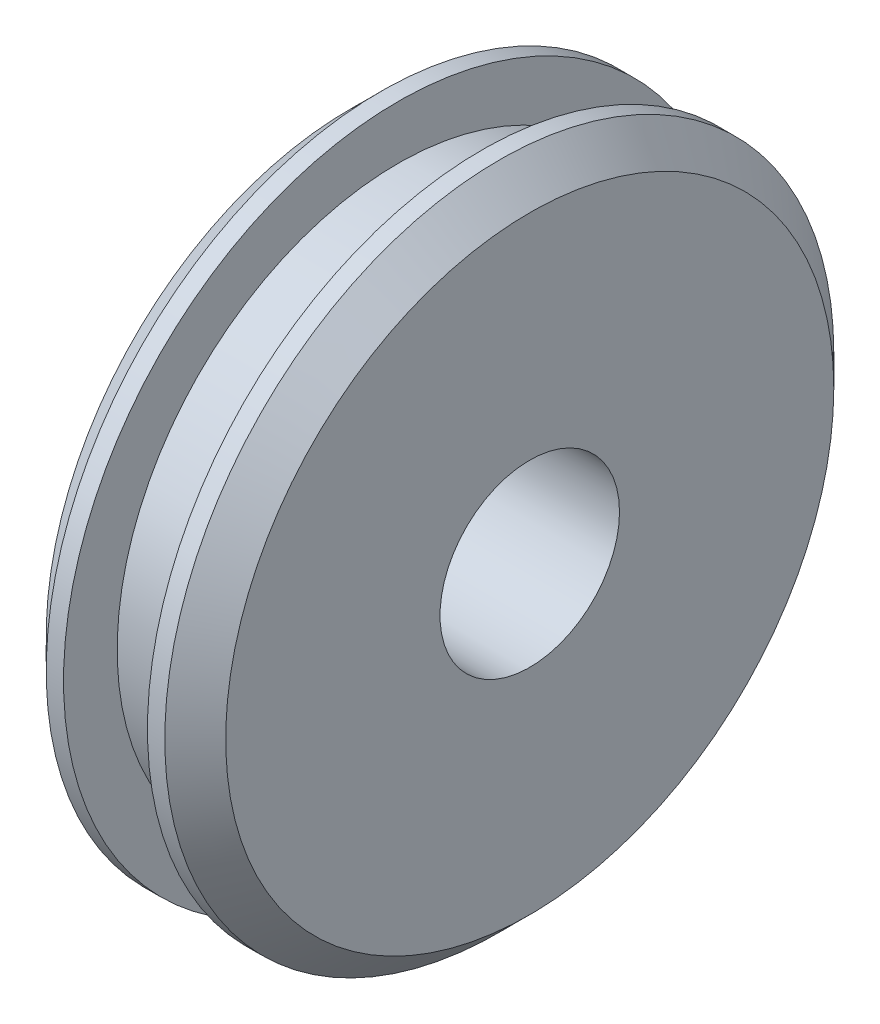
SolidWorks part; units mm, degrees
ref_plane "Front Plane" through (0, 0, 0) normal (0, 0, 1) x (1, 0, 0)
ref_plane "Top Plane" through (0, 0, 0) normal (0, 1, 0) x (1, 0, 0)
ref_plane "Right Plane" through (0, 0, 0) normal (1, 0, 0) x (0, 0, -1)
sketch "Sketch2" plane through (0, 0, 0) normal (0, 0, 1) x (1, 0, 0)
  line L0 (0, 0) -> (-10.16, 0)
  line L2 (-8.4361, 18.9336) -> (-7.4549, 18.9336)
  line L3 (-7.4549, 18.9336) -> (-7.4549, 15.8983)
  line L4 (-7.4549, 15.8983) -> (-2.7051, 15.8983)
  line L5 (-2.7051, 15.8983) -> (-2.7051, 18.9336)
  line L6 (-2.7051, 18.9336) -> (-1.7239, 18.9336)
  line L8 (-1.7239, 18.9336) -> (0, 17.2097)
  line L9 (0, 17.2097) -> (0, 0)
  line L10 (-8.4361, 18.9336) -> (-10.16, 17.2097)
  line L11 (-10.16, 17.2097) -> (-10.16, 0)
  point P15 (-5.08, 15.8983)
  point P16 (-5.08, 0)
  dimension "D1" = 19.0119
  dimension "D2" = 10.16
  dimension "D3" = 4.7498
  dimension "D4" = 45
  dimension "D5" = 90
  dimension "D6" = 3.0353
revolve "Revolve1" add sketch "Sketch2" angle 360 about L0
sketch "Sketch3" plane through (0, 0, 0) normal (1, 0, 0) x (0, 0, -1)
  circle A0 centre (0, 0) radius 5.08
  dimension "D1" = 10.16
extrude "Cut-Extrude1" cut sketch "Sketch3" against normal through all
equation "\"D6@Sketch2\"=(1.497-1.258)/2"
